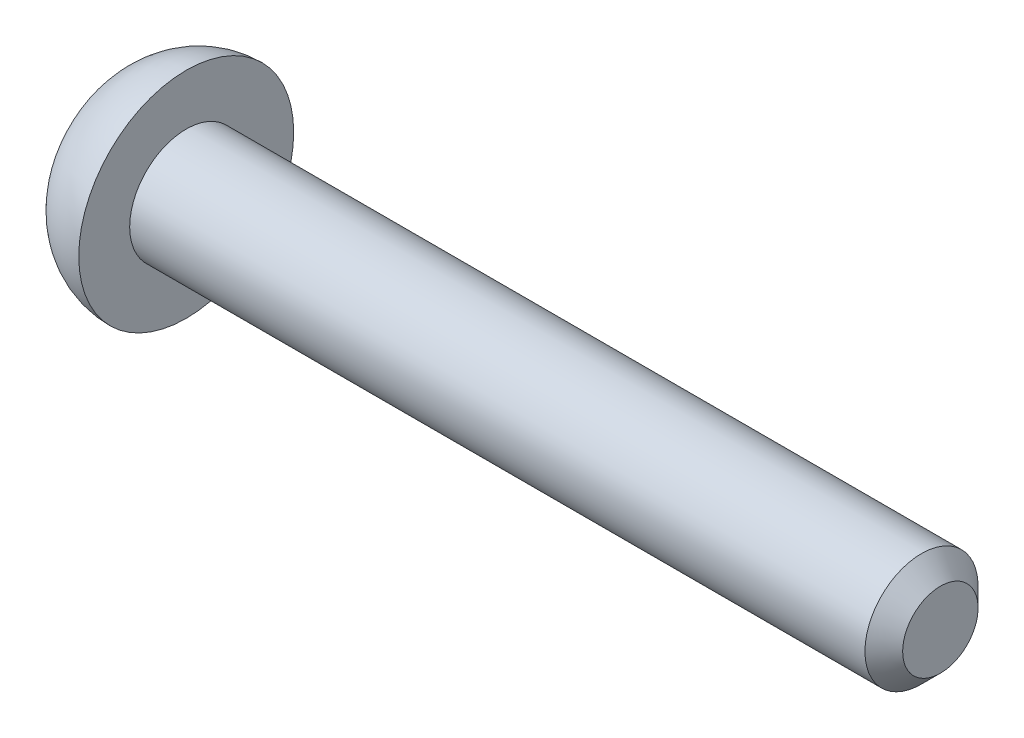
SolidWorks part; units mm, degrees
ref_plane "Front Plane" through (0, 0, 0) normal (0, 0, 1) x (1, 0, 0)
ref_plane "Top Plane" through (0, 0, 0) normal (0, 1, 0) x (1, 0, 0)
ref_plane "Right Plane" through (0, 0, 0) normal (1, 0, 0) x (0, 0, -1)
sketch "Sketch2" plane through (0, 0, 0) normal (0, 1, 0) x (1, 0, 0)
  line L0 (0, 0) -> (0, 1.5)
  line L1 (0, -3.135) -> (0, 3.135) construction
  line L2 (0, 1.5) -> (-20, 1.5)
  line L3 (-20, 1.5) -> (-20, 0) construction
  line L4 (-3.135, 0) -> (3.135, 0) construction
  line L5 (-21.65, 2.049) -> (-21.65, 0)
  line L6 (-21.65, 0) -> (0, 0)
  line L7 (-20, 2.85) -> (-20, 1.5)
  arc A0 (-21.65, 2.049) -> (-20, 2.85) centre (-20, 0.75) cw
  dimension "D2" = 20
  dimension "D3" = 2.85
  dimension "D1" = 1.65
  dimension "D4" = 1.5
revolve "Revolve1" add sketch "Sketch2" angle 360 about L6
chamfer "Chamfer1" distance 0.5 angle 45 1 edges at (0, 0, 1.5)
sketch "Sketch4" plane through (-21.65, 0, 0) normal (-1, 0, 0) x (0, 0, 1)
  line L1 (0.8389, 1.453) -> (-0.8389, 1.453) construction
  line L2 (-0.8389, 1.453) -> (-1.6778, 0) construction
  line L3 (-1.6778, 0) -> (-0.8389, -1.453) construction
  line L4 (-0.8389, -1.453) -> (0.8389, -1.453) construction
  line L5 (0.8389, -1.453) -> (1.6778, 0) construction
  line L6 (1.6778, 0) -> (0.8389, 1.453) construction
  circle A0 centre (0, 0) radius 1.453 construction
  arc A1 (-1.342, 0.0907) -> (-0.7496, 1.1169) centre (-1.7745, 1.0245) ccw
  arc A2 (-0.5924, 1.2076) -> (0.5924, 1.2076) centre (0, 2.049) ccw
  arc A3 (0.7496, 1.1169) -> (1.342, 0.0907) centre (1.7745, 1.0245) ccw
  arc A4 (1.342, -0.0907) -> (0.7496, -1.1169) centre (1.7745, -1.0245) ccw
  arc A5 (-0.5924, -1.2076) -> (0.5924, -1.2076) centre (0, -2.049) cw
  arc A6 (-0.7496, -1.1169) -> (-1.342, -0.0907) centre (-1.7745, -1.0245) ccw
  circle A7 centre (0, 0) radius 2.049 construction
  arc A8 (0.7496, 1.1169) -> (0.5924, 1.2076) centre (0.65, 1.1258) ccw
  arc A9 (1.342, -0.0907) -> (1.342, 0.0907) centre (1.3, 0) ccw
  arc A10 (0.7496, -1.1169) -> (0.5924, -1.2076) centre (0.65, -1.1258) cw
  arc A11 (-0.7496, -1.1169) -> (-0.5924, -1.2076) centre (-0.65, -1.1258) ccw
  arc A12 (-1.342, 0.0907) -> (-1.342, -0.0907) centre (-1.3, 0) ccw
  arc A13 (-0.7496, 1.1169) -> (-0.5924, 1.2076) centre (-0.65, 1.1258) cw
  circle A14 centre (0, 0) radius 2.049 construction
  point P40 (2.049, 0)
  dimension "D1" = 0.1
  dimension "D2" = 2.6
extrude "Cut-Extrude1" cut sketch "Sketch4" against normal blind 1
equation "\"d1\"= 3"
equation "\"l\"= 20"
equation "\"d2\"= 5.7"
equation "\"t\"= 1"
equation "\"k\"=1.65"
equation "\"A\"=2.8"
equation "\"D3@Sketch2\"=\"d2\" / 2"
equation "\"D1@Sketch2\"= \"k\""
equation "\"D4@Sketch2\"=\"d1\" / 2"
equation "\"D2@Sketch4\"= \"A\" - 2 * \"D1@Sketch4\""
equation "\"D1@Cut-Extrude1\"= \"t\""
equation "\"D2@Sketch2\"=\"l\""
